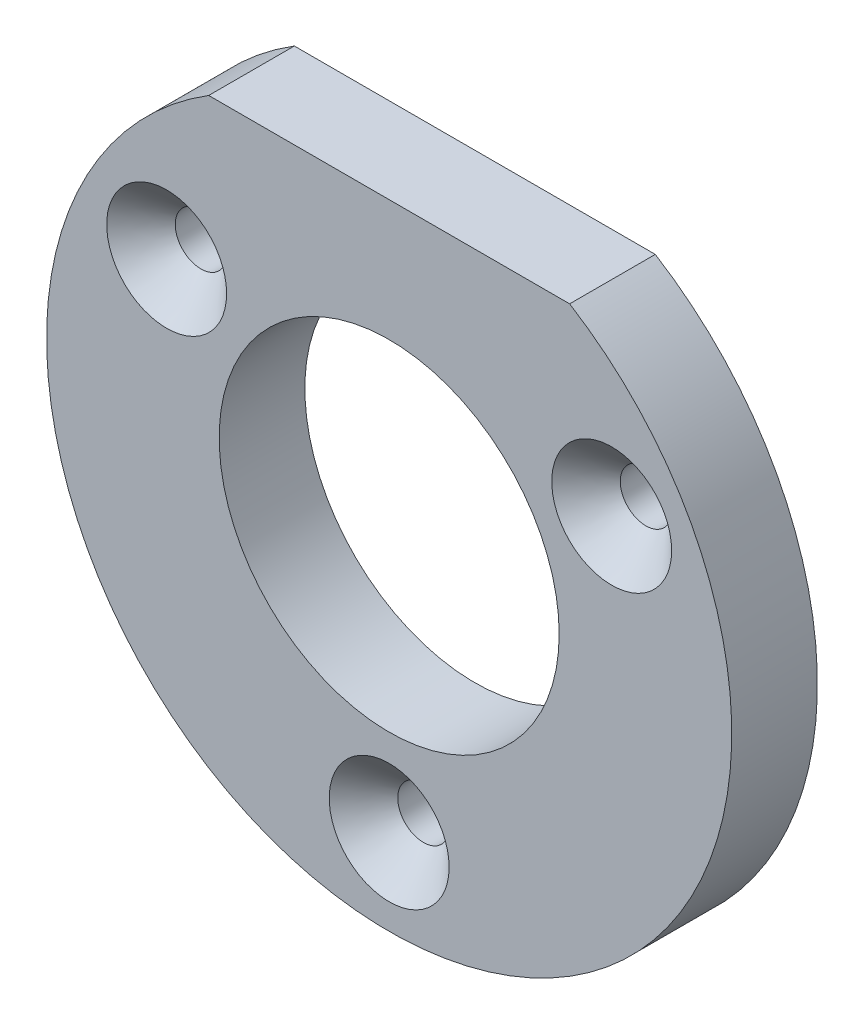
SolidWorks part; units mm, degrees
ref_plane "Front Plane" through (0, 0, 0) normal (0, 0, 1) x (1, 0, 0)
ref_plane "Top Plane" through (0, 0, 0) normal (0, 1, 0) x (1, 0, 0)
ref_plane "Right Plane" through (0, 0, 0) normal (1, 0, 0) x (0, 0, -1)
sketch "Sketch1" plane through (0, 0, 0) normal (0, 0, 1) x (1, 0, 0)
  line L0 (10.5357, 17) -> (-10.5357, 17)
  circle A0 centre (0, 0) radius 9.925
  arc A1 (-10.5357, 17) -> (10.5357, 17) centre (0, 0) ccw
  dimension "D1" = 19.85
  dimension "D2" = 40
  dimension "D3" = 17
extrude "Boss-Extrude1" add sketch "Sketch1" along normal blind 5
sketch "Sketch2" plane through (0, 0, 5) normal (0, 0, 1) x (1, 0, 0)
  line L0 (10.5357, 17) -> (-10.5357, 17) construction
  circle A0 centre (0, -15) radius 1.5
  dimension "D1" = 3
  dimension "D2" = 15
  dimension "D3" = 32
extrude "Cut-Extrude1" cut sketch "Sketch2" against normal through all
pattern_circular "CirPattern1" count 3 over 360 about axis through (0, 0, 0) along (0, 0, 1) of "Cut-Extrude1"
chamfer "Chamfer1" distance 2 angle 45 3 edges at (1.5, -15, 5) (12.2404, 8.799, 5) (-13.7404, 6.201, 5)
